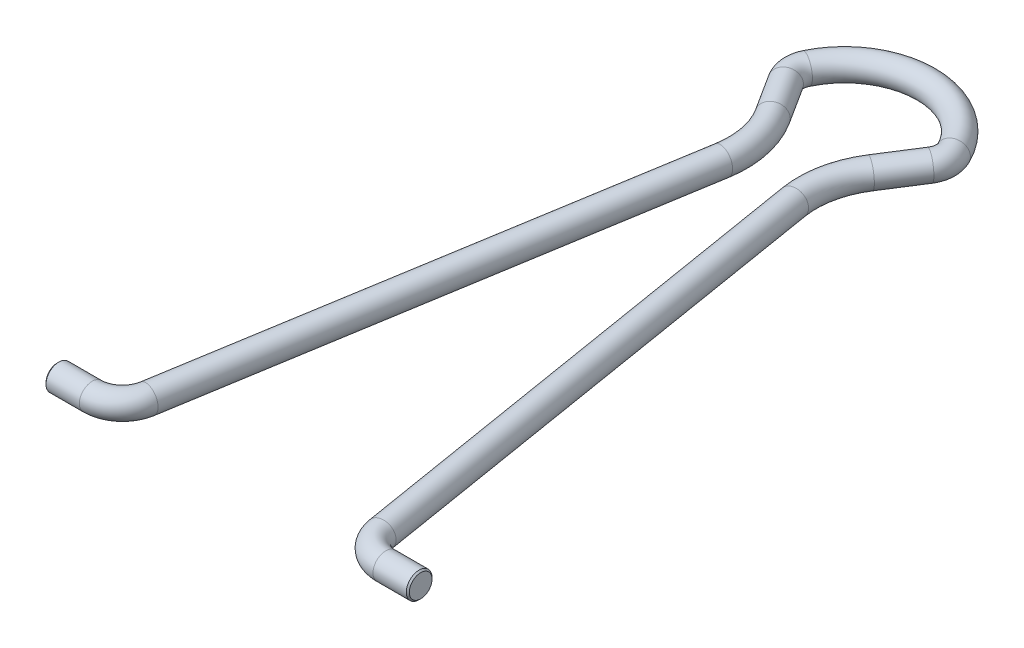
SolidWorks part; units mm, degrees
ref_plane "Front Plane" through (0, 0, 0) normal (0, 0, 1) x (1, 0, 0)
ref_plane "Top Plane" through (0, 0, 0) normal (0, 1, 0) x (1, 0, 0)
ref_plane "Right Plane" through (0, 0, 0) normal (1, 0, 0) x (0, 0, -1)
sketch "Sketch1" plane through (0, 0, 0) normal (0, 1, 0) x (1, 0, 0)
  line L0 (-4.7648, 0.8777) -> (-3.2333, -1.5243)
  line L1 (0, 0) -> (0, 19.5587) construction
  line L2 (-2.3717, -5.7222) -> (-7.7248, -38.3241)
  line L3 (-9.6984, -40) -> (-12, -40)
  line L4 (-3.5, 1.6841) -> (-5, 1.6841) construction
  line L5 (3.5, 1.6841) -> (5, 1.6841) construction
  line L6 (9.6984, -40) -> (12, -40)
  line L7 (2.3717, -5.7222) -> (7.7248, -38.3241)
  line L8 (4.7648, 0.8777) -> (3.2333, -1.5243)
  arc A0 (4.8517, 2.3345) -> (-4.8517, 2.3345) centre (0, 0) ccw
  arc A1 (-4.8517, 2.3345) -> (-4.7648, 0.8777) centre (-3.5, 1.6841) ccw
  arc A2 (-3.2333, -1.5243) -> (-2.3717, -5.7222) centre (-8.2924, -4.75) cw
  arc A3 (-7.7248, -38.3241) -> (-9.6984, -40) centre (-9.6984, -38) cw
  arc A4 (7.7248, -38.3241) -> (9.6984, -40) centre (9.6984, -38) ccw
  arc A5 (3.2333, -1.5243) -> (2.3717, -5.7222) centre (8.2924, -4.75) ccw
  arc A6 (4.8517, 2.3345) -> (4.7648, 0.8777) centre (3.5, 1.6841) cw
  point P14 (-2, -3.4585)
  point P16 (-8, -40)
  point P28 (8, -40)
  point P29 (2, -3.4585)
  dimension "D1" = 3
  dimension "D2" = 7
  dimension "D9" = 6
  dimension "D10" = 2
  dimension "D3" = 5.3841
  dimension "D5" = 40
  dimension "D4" = 4.75
  dimension "D6" = 2
  dimension "D7" = 8
  dimension "D8" = 4
ref_plane "Plane1" through (-12, 0, 40) normal (-1, 0, 0) x (0, 0, 1)
sketch "Sketch2" plane through (-12, 0, 40) normal (-1, 0, 0) x (0, 0, 1)
  circle A0 centre (0, 0) radius 0.85
  dimension "D1" = 1.7
sweep "Sweep2" add profiles "Sketch2" path "Sketch1"
chamfer "Chamfer1" distance 0.1 angle 45 2 edges at (-12, 0, 40.85) (12, 0, 40.85)
